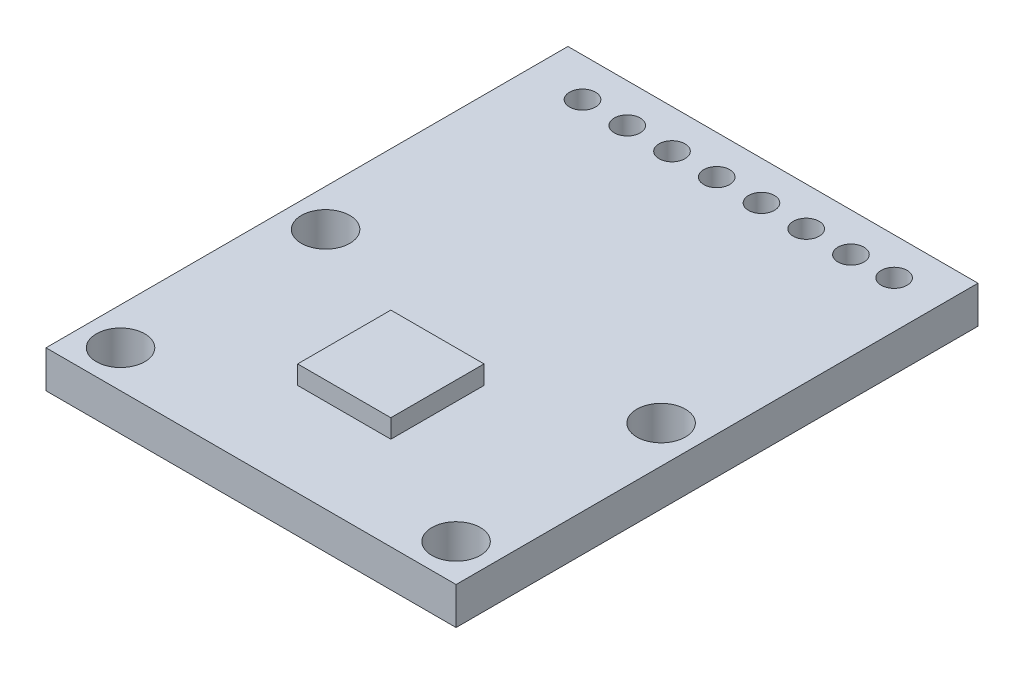
SolidWorks part; units mm, degrees
ref_plane "Front Plane" through (0, 0, 0) normal (0, 0, 1) x (1, 0, 0)
ref_plane "Top Plane" through (0, 0, 0) normal (0, 1, 0) x (1, 0, 0)
ref_plane "Right Plane" through (0, 0, 0) normal (1, 0, 0) x (0, 0, -1)
sketch "Sketch2" plane through (0, 0, 0) normal (0, 1, 0) x (1, 0, 0)
  line L1 (-11, -14) -> (11, -14)
  line L2 (-11, -14) -> (-11, 14)
  line L3 (-11, 14) -> (11, 14)
  line L4 (11, -14) -> (11, 14)
  line L5 (-11, -14) -> (11, 14) construction
  line L6 (-11, 14) -> (11, -14) construction
  line L7 (9, -12) -> (-9, -12) construction
  line L8 (9, -12) -> (9, -1) construction
  line L9 (9, -1) -> (-9, -1) construction
  line L10 (-9, -12) -> (-9, -1) construction
  circle A0 centre (9, -12) radius 1.3
  circle A2 centre (-9, -12) radius 1.3
  circle A3 centre (-9, -1) radius 1.3
  circle A4 centre (9, -1) radius 1.3
  point P0 (0, 0)
  dimension "D6" = 2.6
  dimension "D1" = 28
  dimension "D2" = 22
  dimension "D3" = 11
  dimension "D4" = 2
  dimension "D5" = 2
  dimension "D7" = 2
extrude "MainBody" add sketch "Sketch2" along normal blind 2 contours L1 L4 L3 L2 A4 A3 A2 A0
sketch "Sketch3" plane through (0, 2, 0) normal (0, 1, 0) x (1, 0, 0)
  line L0 (9, -6.5) -> (-9, -6.5) construction
  line L5 (-2.5, -9) -> (2.5, -9)
  line L6 (-2.5, -9) -> (-2.5, -4)
  line L7 (-2.5, -4) -> (2.5, -4)
  line L8 (2.5, -9) -> (2.5, -4)
  line L9 (-2.5, -9) -> (2.5, -4) construction
  line L10 (-2.5, -4) -> (2.5, -9) construction
  line L11 (9, -12) -> (9, -1) construction
  line L12 (-9, -12) -> (-9, -1) construction
  point P0 (0, -6.5)
  point P5 (0, 0)
  dimension "D1" = 5
  dimension "D2" = 5
extrude "chip" add sketch "Sketch3" along normal blind 1
sketch "Sketch4" plane through (0, 2, 0) normal (0, 1, 0) x (1, 0, 0)
  line L0 (11, -14) -> (11, 14) construction
  line L1 (-9.6378, 13) -> (10, 13) construction
  line L2 (-9.6378, 13) -> (-9.6378, 11) construction
  line L3 (-9.6378, 11) -> (10, 11) construction
  line L4 (10, 13) -> (10, 11) construction
  line L5 (-11, -14) -> (-11, 14) construction
  line L6 (-11, 14) -> (11, 14) construction
  line L7 (-9.6378, 12) -> (10, 12) construction
  line L8 (-8.1378, 11.921) -> (-5.7378, 11.921) construction
  circle A0 centre (-8.1378, 11.921) radius 0.6956
  circle A1 centre (8.5, 12) radius 0.6956
  circle A8 centre (-5.7378, 11.921) radius 0.6956
  circle A9 centre (-3.3378, 11.921) radius 0.6956
  circle A10 centre (-0.9378, 11.921) radius 0.6956
  circle A11 centre (1.4622, 11.921) radius 0.6956
  circle A12 centre (3.8622, 11.921) radius 0.6956
  circle A13 centre (6.2622, 11.921) radius 0.6956
  dimension "D4" = 2
  dimension "D1" = 1
  dimension "D2" = 1.3622
  dimension "D3" = 1
  dimension "D5" = 1.5
  dimension "D6" = 1.5
  dimension "D8" = 2.4
  dimension "D7" = 7
extrude "Cut-Extrude1" cut sketch "Sketch4" against normal through all
equation "\"D5@Sketch2\"=\"D4@Sketch2\""
equation "\"D7@Sketch2\"=\"D4@Sketch2\""
equation "\"D6@Sketch4\"=\"D5@Sketch4\""
